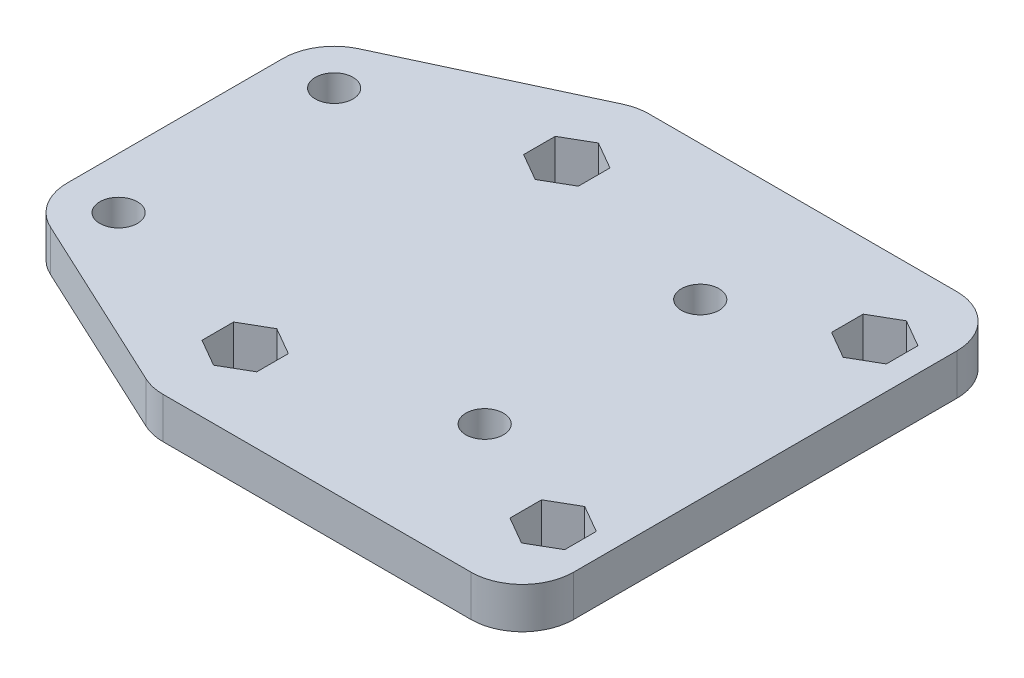
SolidWorks part; units mm, degrees
ref_plane "Front Plane" through (0, 0, 0) normal (0, 0, 1) x (1, 0, 0)
ref_plane "Top Plane" through (0, 0, 0) normal (0, 1, 0) x (1, 0, 0)
ref_plane "Right Plane" through (0, 0, 0) normal (1, 0, 0) x (0, 0, -1)
sketch "Sketch1" plane through (0, 0, 0) normal (0, 1, 0) x (1, 0, 0)
  line L0 (-28.5, -23.5) -> (-23.5, -23.5) construction
  line L7 (16.5, -23.5) -> (21.5, -23.5) construction
  line L10 (16.5, 23.5) -> (21.5, 23.5) construction
  line L13 (-28.5, 23.5) -> (-23.5, 23.5) construction
  line L16 (-59.75, 15.75) -> (-59.75, -15.75)
  line L17 (-55.4216, -22.5464) -> (-29.1716, -34.7964)
  line L18 (-26, -35.5) -> (19, -35.5)
  line L19 (26.5, -28) -> (26.5, 28)
  line L20 (19, 35.5) -> (-26, 35.5)
  line L21 (-29.1716, 34.7964) -> (-55.4216, 22.5464)
  circle A0 centre (-52.25, 15.75) radius 2.75
  circle A1 centre (-52.25, -15.75) radius 2.75
  circle A2 centre (1.25, -15.75) radius 2.75
  circle A3 centre (1.25, 15.75) radius 2.75
  circle A4 centre (-26, -23.5) radius 2.5
  circle A5 centre (19, -23.5) radius 2.5
  circle A6 centre (19, 23.5) radius 2.5
  circle A7 centre (-26, 23.5) radius 2.5
  circle A12 centre (-52.25, 15.75) radius 7.5
  circle A13 centre (-52.25, -15.75) radius 7.5
  circle A14 centre (-26, -28) radius 7.5
  circle A15 centre (19, -28) radius 7.5
  circle A16 centre (19, 28) radius 7.5
  circle A17 centre (-26, 28) radius 7.5
  point P6 (0, 0)
  point P7 (-28.5, 23.3453)
  point P15 (-23.509, 22.6692)
  point P16 (-23.5, 23.5)
  point P30 (16.5, 23.2645)
  point P39 (21.5, 23.5)
  point P54 (-28.5, -23.5)
  point P57 (-23.5, -23.5)
  point P61 (16.5, -23.5)
  point P78 (21.5, -23.5)
  point P84 (2.2662, 15.9974)
  point P87 (3.4635, -17.0055)
  point P92 (-52.25, 15.75)
  point P94 (-52.25, 15.75)
  dimension "D1" = 15
extrude "Boss-Extrude1" add sketch "Sketch1" along normal blind 6 contours A12 A0 | A17 L21 A12 L16 A13 L17 A14 L18 A15 L19 A16 L20 A3 A2 | A13 A1 | A14 A4 | A15 A5 | A16 A6 | A17 A7
sketch "Sketch2" plane through (0, 6, 0) normal (0, 1, 0) x (1, 0, 0)
  line L1 (-26, 18.8812) -> (-22, 21.1906)
  line L2 (-22, 21.1906) -> (-22, 25.8094)
  line L3 (-22, 25.8094) -> (-26, 28.1188)
  line L4 (-26, 28.1188) -> (-30, 25.8094)
  line L5 (-30, 25.8094) -> (-30, 21.1906)
  line L6 (-30, 21.1906) -> (-26, 18.8812)
  line L7 (-26, -18.8812) -> (-30, -21.1906)
  line L8 (-30, -21.1906) -> (-30, -25.8094)
  line L9 (-30, -25.8094) -> (-26, -28.1188)
  line L10 (-26, -28.1188) -> (-22, -25.8094)
  line L11 (-22, -25.8094) -> (-22, -21.1906)
  line L12 (-22, -21.1906) -> (-26, -18.8812)
  line L13 (15, -25.8094) -> (19, -28.1188)
  line L14 (19, -28.1188) -> (23, -25.8094)
  line L15 (23, -25.8094) -> (23, -21.1906)
  line L16 (23, -21.1906) -> (19, -18.8812)
  line L17 (19, -18.8812) -> (15, -21.1906)
  line L18 (15, -21.1906) -> (15, -25.8094)
  line L19 (19, 18.8812) -> (23, 21.1906)
  line L20 (23, 21.1906) -> (23, 25.8094)
  line L21 (23, 25.8094) -> (19, 28.1188)
  line L22 (19, 28.1188) -> (15, 25.8094)
  line L23 (15, 25.8094) -> (15, 21.1906)
  line L24 (15, 21.1906) -> (19, 18.8812)
  circle A0 centre (-26, 23.5) radius 4 construction
  circle A1 centre (-26, -23.5) radius 4 construction
  circle A2 centre (19, -23.5) radius 4 construction
  circle A3 centre (19, 23.5) radius 4 construction
  dimension "D1" = 8
extrude "Cut-Extrude1" cut sketch "Sketch2" against normal through all and the other way through all
